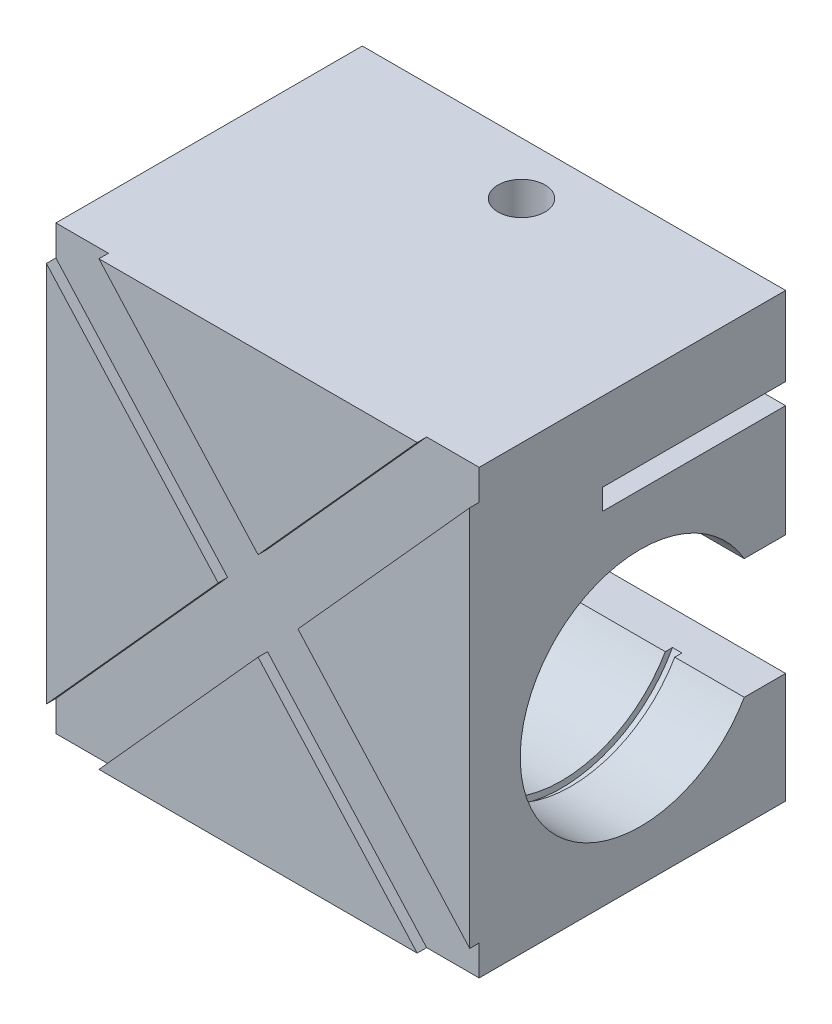
SolidWorks part; units mm, degrees
material "AISI 1020"
ref_plane "Front Plane" through (0, 0, 0) normal (0, 0, 1) x (1, 0, 0)
ref_plane "Top Plane" through (0, 0, 0) normal (0, 1, 0) x (1, 0, 0)
ref_plane "Right Plane" through (0, 0, 0) normal (1, 0, 0) x (0, 0, -1)
sketch "Sketch3" plane through (0, 0, 0) normal (0, 1, 0) x (1, 0, 0)
  line L1 (0, 0) -> (67, 0)
  line L2 (0, 0) -> (0, 50)
  line L3 (0, 50) -> (67, 50)
  line L4 (67, 0) -> (67, 50)
  dimension "D1" = 50
  dimension "D2" = 67
extrude "Boss-Extrude1" add sketch "Sketch3" against normal blind 70 contours L2 L1 L4 L3
sketch "Sketch4" plane through (0, 0, 0) normal (0, 1, 0) x (1, 0, 0)
  line L0 (0, 0) -> (0, 50) construction
  line L1 (0, 50) -> (67, 50) construction
  circle A0 centre (33.5, 41.7) radius 3.7202
  dimension "D1" = 33.5
  dimension "D2" = 8.3
sketch "Sketch5" plane through (0, 0, 0) normal (0, 0, 1) x (1, 0, 0)
  line L0 (0, -65.2) -> (0, -70)
  line L1 (0, -70) -> (0, 0) construction
  line L2 (0, -65.2) -> (8.3138, -70) construction
  line L3 (0, -70) -> (67, -70) construction
  line L4 (0, -65.2) -> (27.1829, -35)
  line L5 (0, 0) -> (67, 0) construction
  line L6 (8.3138, -70) -> (33.5, -42.0183)
  line L7 (67, -70) -> (67, 0) construction
  line L8 (67, 0) -> (67, -4.8) construction
  line L9 (0, -70) -> (8.3138, -70)
  line L10 (58.6862, 0) -> (67, -4.8) construction
  line L11 (58.6862, 0) -> (67, 0)
  line L12 (0, 0) -> (0, -4.8)
  line L13 (0, 0) -> (8.3138, 0)
  line L14 (0, -4.8) -> (8.3138, 0) construction
  line L15 (8.3138, 0) -> (33.5, -27.9817)
  line L16 (67, -65.2) -> (67, -70)
  line L17 (67, -70) -> (58.6862, -70)
  line L18 (58.6862, -70) -> (33.5, -42.0183)
  line L19 (67, -65.2) -> (58.6862, -70) construction
  line L20 (39.8171, -35) -> (67, -65.2)
  line L21 (27.1829, -35) -> (0, -4.8)
  line L22 (33.5, -27.9817) -> (58.6862, 0)
  line L23 (39.8171, -35) -> (67, -4.8)
  dimension "D1" = 4.8
  dimension "D2" = 9.6
  dimension "D3" = 4.8
  dimension "D4" = 9.6
  dimension "D5" = 9.6
  dimension "D6" = 4.8
  dimension "D7" = 9.6
  dimension "D8" = 4.8
extrude "Cut-Extrude1" cut sketch "Sketch5" against normal blind 1.5 and the other way through all
sketch "Sketch6" plane through (67, 0, 0) normal (1, 0, 0) x (0, 0, -1)
  line L0 (0, -65.2) -> (0, -4.8) construction
  line L1 (1.5, -70) -> (50, -70) construction
  line L3 (50, -70) -> (50, 0) construction
  line L8 (43.4545, -33.5) -> (50, -33.5)
  line L9 (50, -33.5) -> (50, -52.5)
  line L10 (50, -52.5) -> (43.4545, -52.5)
  arc A0 (43.4545, -33.5) -> (43.4545, -52.5) centre (27, -43) ccw
  point P1 (50, -43)
  dimension "D3" = 38
  dimension "D1" = 27
  dimension "D2" = 27
  dimension "D7" = 19
extrude "Cut-Extrude3" cut sketch "Sketch6" against normal through all contours A0 L10 L9 L8
sketch "Sketch8" plane through (67, 0, 0) normal (1, 0, 0) x (0, 0, -1)
  line L0 (50, -33.5) -> (50, 0) construction
  line L1 (50, -12.5) -> (21, -12.5)
  line L2 (50, -12.5) -> (50, -15.8)
  line L3 (50, -15.8) -> (21, -15.8)
  line L4 (21, -12.5) -> (21, -15.8)
  line L6 (1.5, 0) -> (50, 0) construction
  dimension "D1" = 12.5
  dimension "D2" = 3.3
  dimension "D3" = 29
extrude "Cut-Extrude4" cut sketch "Sketch8" against normal through all
extrude "Cut-Extrude5" cut sketch "Sketch4" against normal up to next
ref_plane "Plane1" through (54.5, 0, 0) normal (1, 0, 0) x (0, 0, -1)
sketch "Sketch9" plane through (54.5, 0, 0) normal (1, 0, 0) x (0, 0, -1)
  line L15 (50, -15.8) -> (21, -15.8)
  line L16 (21, -15.8) -> (21, -12.5)
  line L17 (21, -12.5) -> (50, -12.5)
  line L18 (50, -12.5) -> (50, 0)
  line L19 (50, 0) -> (1.5, 0)
  line L20 (1.5, 0) -> (1.5, -4.8)
  line L21 (1.5, -4.8) -> (0, -4.8)
  line L22 (0, -4.8) -> (0, -65.2)
  line L23 (0, -65.2) -> (1.5, -65.2)
  line L24 (1.5, -65.2) -> (1.5, -70)
  line L25 (1.5, -70) -> (50, -70)
  line L26 (50, -70) -> (50, -52.5)
  line L27 (50, -52.5) -> (43.4545, -52.5)
  line L28 (43.4545, -33.5) -> (50, -33.5)
  line L29 (50, -33.5) -> (50, -15.8)
  line L30 (50, -15.8) -> (21, -15.8) construction
  line L31 (21, -15.8) -> (21, -12.5) construction
  line L32 (21, -12.5) -> (50, -12.5) construction
  line L33 (50, -12.5) -> (50, 0) construction
  line L34 (50, 0) -> (1.5, 0) construction
  line L35 (1.5, 0) -> (1.5, -4.8) construction
  line L36 (1.5, -4.8) -> (0, -4.8) construction
  line L37 (0, -4.8) -> (0, -65.2) construction
  line L38 (0, -65.2) -> (1.5, -65.2) construction
  line L39 (1.5, -65.2) -> (1.5, -70) construction
  line L40 (1.5, -70) -> (50, -70) construction
  line L41 (50, -70) -> (50, -52.5) construction
  line L42 (50, -52.5) -> (43.4545, -52.5) construction
  line L43 (43.4545, -33.5) -> (50, -33.5) construction
  line L44 (50, -33.5) -> (50, -15.8) construction
  circle A0 centre (27, -43) radius 20
  arc A1 (43.4545, -33.5) -> (43.4545, -52.5) centre (27, -43) ccw
  arc A2 (43.4545, -33.5) -> (43.4545, -52.5) centre (27, -43) ccw construction
  dimension "D2" = 40
  dimension "D1" = 0
extrude "Cut-Extrude6" cut sketch "Sketch9" along normal blind 1.5
ref_plane "Plane2" through (12.5, 0, 0) normal (1, 0, 0) x (0, 0, -1)
sketch "Sketch10" plane through (12.5, 0, 0) normal (1, 0, 0) x (0, 0, -1)
  line L15 (50, -15.8) -> (21, -15.8)
  line L16 (21, -15.8) -> (21, -12.5)
  line L17 (21, -12.5) -> (50, -12.5)
  line L18 (50, -12.5) -> (50, 0)
  line L19 (50, 0) -> (1.5, 0)
  line L20 (1.5, 0) -> (1.5, -4.8)
  line L21 (1.5, -4.8) -> (0, -4.8)
  line L22 (0, -4.8) -> (0, -65.2)
  line L23 (0, -65.2) -> (1.5, -65.2)
  line L24 (1.5, -65.2) -> (1.5, -70)
  line L25 (1.5, -70) -> (50, -70)
  line L26 (50, -70) -> (50, -52.5)
  line L27 (50, -52.5) -> (43.4545, -52.5)
  line L28 (43.4545, -33.5) -> (50, -33.5)
  line L29 (50, -33.5) -> (50, -15.8)
  line L30 (50, -15.8) -> (21, -15.8) construction
  line L31 (21, -15.8) -> (21, -12.5) construction
  line L32 (21, -12.5) -> (50, -12.5) construction
  line L33 (50, -12.5) -> (50, 0) construction
  line L34 (50, 0) -> (1.5, 0) construction
  line L35 (1.5, 0) -> (1.5, -4.8) construction
  line L36 (1.5, -4.8) -> (0, -4.8) construction
  line L37 (0, -4.8) -> (0, -65.2) construction
  line L38 (0, -65.2) -> (1.5, -65.2) construction
  line L39 (1.5, -65.2) -> (1.5, -70) construction
  line L40 (1.5, -70) -> (50, -70) construction
  line L41 (50, -70) -> (50, -52.5) construction
  line L42 (50, -52.5) -> (43.4545, -52.5) construction
  line L43 (43.4545, -33.5) -> (50, -33.5) construction
  line L44 (50, -33.5) -> (50, -15.8) construction
  circle A0 centre (27, -43) radius 20
  arc A1 (43.4545, -33.5) -> (43.4545, -52.5) centre (27, -43) ccw
  arc A2 (43.4545, -33.5) -> (43.4545, -52.5) centre (27, -43) ccw construction
  dimension "D2" = 40
  dimension "D1" = 0
extrude "Cut-Extrude7" cut sketch "Sketch10" against normal blind 1.5
